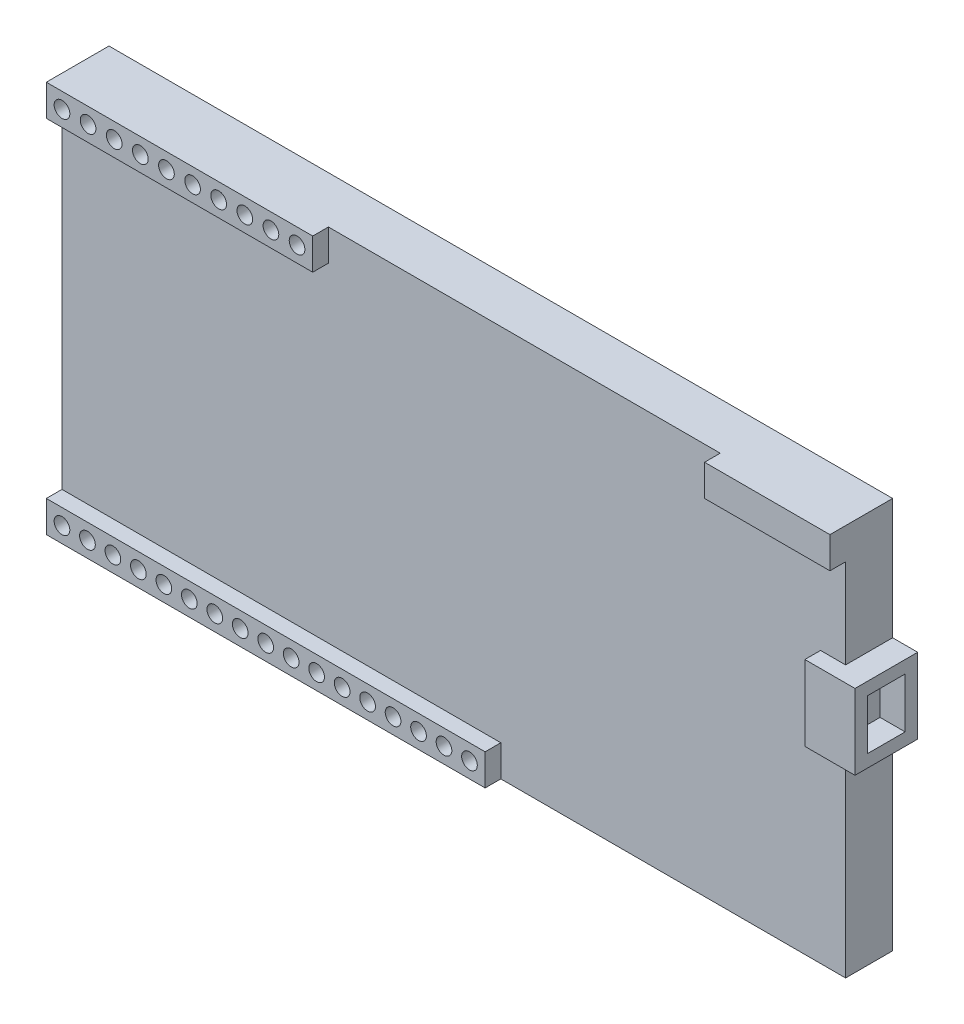
SolidWorks part; units mm, degrees
ref_plane "Front Plane" through (0, 0, 0) normal (1, 0, 0) x (0, 1, 0)
ref_plane "Top Plane" through (0, 0, 0) normal (0, 0, 1) x (0, 1, 0)
ref_plane "Right Plane" through (0, 0, 0) normal (0, 1, 0) x (-1, 0, 0)
sketch "Sketch1" plane through (0, 0, 0) normal (0, 0, 1) x (0, 1, 0)
  line L1 (62.5, -125) -> (-62.5, -125)
  line L2 (62.5, -125) -> (62.5, 125)
  line L3 (62.5, 125) -> (-62.5, 125)
  line L4 (-62.5, -125) -> (-62.5, 125)
  line L5 (62.5, -125) -> (-62.5, 125) construction
  line L6 (62.5, 125) -> (-62.5, -125) construction
  point P0 (0, 0)
  dimension "D1" = 125
  dimension "D2" = 250
extrude "Boss-Extrude1" add sketch "Sketch1" along normal blind 15
sketch "Sketch2" plane through (0, 0, 15) normal (0, 0, 1) x (1, 0, 0)
  line L0 (-125, 57.5) -> (-40, 57.5) construction
  line L1 (-125, 62.5) -> (-40, 62.5)
  line L2 (-125, 62.5) -> (-125, 52.5)
  line L3 (-125, 52.5) -> (-40, 52.5)
  line L4 (-40, 62.5) -> (-40, 52.5)
  line L5 (-125, -62.5) -> (15, -62.5)
  line L6 (-125, -62.5) -> (-125, -52.5)
  line L7 (-125, -52.5) -> (15, -52.5)
  line L8 (15, -62.5) -> (15, -52.5)
  line L9 (-125, -57.5) -> (15, -57.5) construction
  line L11 (125, 62.5) -> (85, 62.5)
  line L12 (125, 62.5) -> (125, 52.5)
  line L13 (125, 52.5) -> (85, 52.5)
  line L14 (85, 62.5) -> (85, 52.5)
  circle A0 centre (-120, 57.5) radius 2.5
  circle A1 centre (-111.6667, 57.5) radius 2.5
  circle A2 centre (-103.3333, 57.5) radius 2.5
  circle A3 centre (-95, 57.5) radius 2.5
  circle A4 centre (-86.6667, 57.5) radius 2.5
  circle A5 centre (-78.3333, 57.5) radius 2.5
  circle A6 centre (-70, 57.5) radius 2.5
  circle A7 centre (-61.6667, 57.5) radius 2.5
  circle A8 centre (-53.3333, 57.5) radius 2.5
  circle A9 centre (-45, 57.5) radius 2.5
  circle A10 centre (-120, -57.5) radius 2.5
  circle A11 centre (-111.875, -57.5) radius 2.5
  circle A12 centre (-103.75, -57.5) radius 2.5
  circle A13 centre (-95.625, -57.5) radius 2.5
  circle A14 centre (-87.5, -57.5) radius 2.5
  circle A15 centre (-79.375, -57.5) radius 2.5
  circle A16 centre (-71.25, -57.5) radius 2.5
  circle A17 centre (-63.125, -57.5) radius 2.5
  circle A18 centre (-55, -57.5) radius 2.5
  circle A19 centre (-46.875, -57.5) radius 2.5
  circle A20 centre (-38.75, -57.5) radius 2.5
  circle A21 centre (-30.625, -57.5) radius 2.5
  circle A22 centre (-22.5, -57.5) radius 2.5
  circle A23 centre (-14.375, -57.5) radius 2.5
  circle A24 centre (-6.25, -57.5) radius 2.5
  circle A25 centre (1.875, -57.5) radius 2.5
  circle A26 centre (10, -57.5) radius 2.5
  dimension "D5" = 5
  dimension "D9" = 5
  dimension "D1" = 10
  dimension "D2" = 85
  dimension "D3" = 140
  dimension "D4" = 10
  dimension "D6" = 5
  dimension "D8" = 5
  dimension "D10" = 5
  dimension "D12" = 5
  dimension "D13" = 40
  dimension "D14" = 10
  dimension "D7" = 10
  dimension "D11" = 17
extrude "Boss-Extrude2" add sketch "Sketch2" along normal blind 5
sketch "Sketch3" plane through (125, 0, 0) normal (1, 0, 0) x (0, 1, 0)
  line L0 (52.5, 20) -> (62.5, 20) construction
  line L1 (0, 0) -> (24, 0)
  line L2 (0, 0) -> (0, 20)
  line L3 (0, 20) -> (24, 20)
  line L4 (24, 0) -> (24, 20)
  line L5 (4, 16) -> (20, 16)
  line L6 (20, 4) -> (20, 16)
  line L7 (4, 4) -> (20, 4)
  line L8 (4, 4) -> (4, 16)
  dimension "D1" = 24
  dimension "D2" = 4
extrude "Boss-Extrude3" add sketch "Sketch3" along normal blind 8
sketch "Sketch4" plane through (125, 0, 0) normal (-1, 0, 0) x (0, -1, 0)
  line L1 (-24, 20) -> (0, 20)
  line L2 (-24, 20) -> (-24, 0)
  line L3 (-24, 0) -> (0, 0)
  line L4 (0, 20) -> (0, 0)
extrude "Boss-Extrude4" add sketch "Sketch4" along normal blind 8
